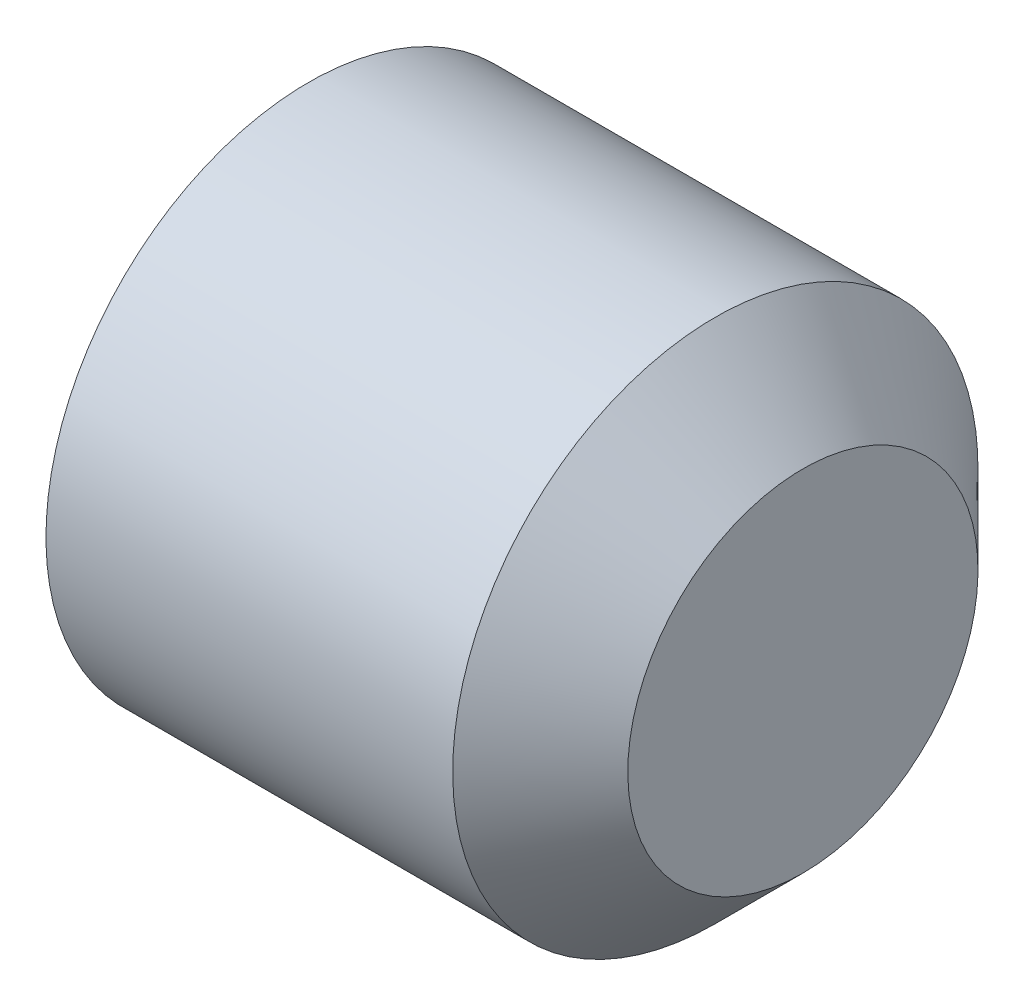
SolidWorks part; units mm, degrees
ref_plane "Plan de face" through (0, 0, 0) normal (0, 0, 1) x (1, 0, 0)
ref_plane "Plan de dessus" through (0, 0, 0) normal (0, 1, 0) x (1, 0, 0)
ref_plane "Plan de droite" through (0, 0, 0) normal (1, 0, 0) x (0, 0, -1)
ref_plane "Plan1" through (0, 0, 0) normal (0, 0, 1) x (1, 0, 0)
sketch "Esquisse1" plane through (0, 0, 0) normal (0, 0, 1) x (1, 0, 0)
  line L0 (3, 0) -> (3, -1)
  line L1 (3, -1) -> (2.5, -1.5)
  line L2 (2.5, -1.5) -> (0.177, -1.5)
  line L3 (0.177, -1.5) -> (0, -1.1935)
  line L4 (0, -1.1935) -> (0, -0.866)
  line L5 (0, -0.866) -> (0.5, 0)
  line L6 (0.5, 0) -> (3, 0)
  line L7 (0.5, 0) -> (3, 0) construction
revolve "Révolution1" add sketch "Esquisse1" angle 360 about L7
cosmetic thread "Représentation de filetage1" parameters "D1"=2.8065, "D2"=2.387
ref_plane "Plan2" through (0, 0, 0) normal (1, 0, 0) x (0, 0, -1)
sketch "Esquisse2" plane through (0, 0, 0) normal (1, 0, 0) x (0, 0, -1)
  line L0 (-0.866, 0) -> (-0.433, -0.75)
  line L1 (-0.433, -0.75) -> (0.433, -0.75)
  line L2 (0.433, -0.75) -> (0.866, 0)
  line L3 (0.866, 0) -> (0.433, 0.75)
  line L4 (0.433, 0.75) -> (-0.433, 0.75)
  line L5 (-0.433, 0.75) -> (-0.866, 0)
extrude "Enlèv. mat.-Extru.1" cut sketch "Esquisse2" along normal blind 1.2
